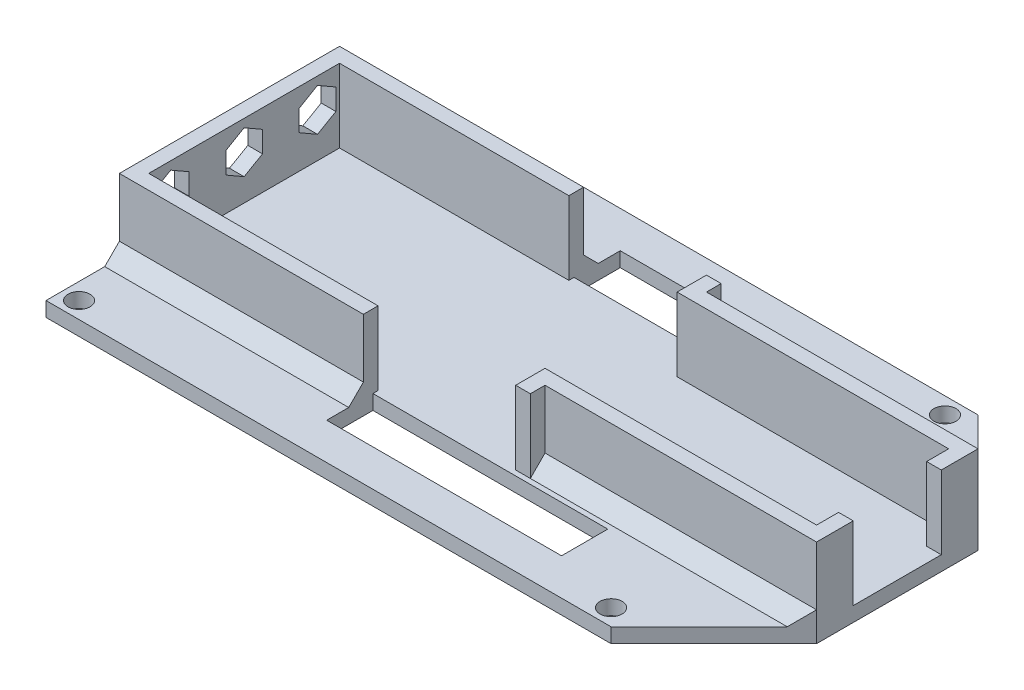
SolidWorks part; units mm, degrees
ref_plane "Front Plane" through (0, 0, 0) normal (0, 0, 1) x (1, 0, 0)
ref_plane "Top Plane" through (0, 0, 0) normal (0, 1, 0) x (1, 0, 0)
ref_plane "Right Plane" through (0, 0, 0) normal (1, 0, 0) x (0, 0, -1)
sketch "Sketch1" plane through (0, 0, 0) normal (0, 1, 0) x (1, 0, 0)
  line L0 (0, 25) -> (0, -25) construction
  line L1 (-38.5, -25) -> (38.5, -25)
  line L2 (-38.5, -25) -> (-38.5, 25)
  line L3 (-38.5, 25) -> (38.5, 25)
  line L4 (38.5, -25) -> (38.5, 25)
  line L5 (-38.5, -25) -> (38.5, 25) construction
  line L6 (-38.5, 25) -> (38.5, -25) construction
  line L7 (-38.5, 0) -> (38.5, 0) construction
  line L8 (-33.5, 20) -> (33.5, 20) construction
  line L9 (33.5, -20) -> (33.5, 20) construction
  line L10 (-33.5, -20) -> (33.5, -20) construction
  line L11 (-33.5, -20) -> (-33.5, 20) construction
  line L12 (26.75, 13.7) -> (-5.25, 13.7)
  line L13 (26.75, -20) -> (-5.25, -20)
  line L14 (26.75, -20) -> (26.75, -13.7)
  line L15 (26.75, -13.7) -> (-5.25, -13.7)
  line L16 (-5.25, -20) -> (-5.25, -13.7)
  line L17 (-5.25, 20) -> (-5.25, 13.7)
  line L18 (26.75, 20) -> (-5.25, 20)
  line L19 (26.75, 20) -> (26.75, 13.7)
  circle A1 centre (-36.25, 22.75) radius 1.5
  circle A2 centre (36.25, 22.75) radius 1.5
  circle A3 centre (36.25, -22.75) radius 1.5
  circle A4 centre (-36.25, -22.75) radius 1.5
  point P0 (0, 0)
  dimension "D3" = 3
  dimension "D4" = 2.25
  dimension "D1" = 77
  dimension "D2" = 50
  dimension "D5" = 2.25
  dimension "D6" = 5
  dimension "D7" = 6.75
  dimension "D8" = 32
  dimension "D9" = 6.3
extrude "Boss-Extrude1" add sketch "Sketch1" along normal blind 2
sketch "Sketch2" plane through (0, 2, 0) normal (0, 1, 0) x (1, 0, 0)
  line L0 (-38.5, 0) -> (38.5, 0) construction
  line L1 (-38.5, 25) -> (-38.5, -25) construction
  line L2 (38.5, -25) -> (38.5, 25) construction
  line L3 (-38.5, -15) -> (-38.5, 15)
  line L4 (-36.5, -13) -> (13.5, -13)
  line L5 (-36.5, -13) -> (-36.5, 13)
  line L6 (-36.5, 13) -> (13.5, 13)
  line L7 (13.5, -13) -> (13.5, -9)
  line L8 (-36.5, -13) -> (13.5, 13) construction
  line L9 (-36.5, 13) -> (13.5, -13) construction
  line L10 (-38.5, 15) -> (-5.25, 15)
  line L11 (15.5, -13) -> (15.5, -11)
  line L12 (-38.5, -15) -> (-5.25, -15)
  line L13 (-5.25, 13) -> (-5.25, 15)
  line L14 (-5.25, 20) -> (-5.25, 13.7) construction
  line L15 (-5.25, -15) -> (-5.25, -13)
  line L16 (13.5, 13) -> (15.5, 13)
  line L17 (13.5, -13) -> (15.5, -13)
  line L18 (-38.5, -15) -> (15.5, -15) construction
  line L19 (15.5, -15) -> (15.5, 15) construction
  line L20 (-38.5, 15) -> (15.5, 15) construction
  line L22 (13.5, -9) -> (50.5, -9)
  line L24 (13.5, 9) -> (50.5, 9)
  line L25 (50.5, -9) -> (50.5, -6)
  line L26 (13.5, -9) -> (50.5, 9) construction
  line L27 (13.5, 9) -> (50.5, -9) construction
  line L29 (52.5, -11) -> (52.5, -6)
  line L31 (15.5, 11) -> (52.5, 11)
  line L32 (11.5, 11) -> (52.5, 11) construction
  line L33 (15.5, -11) -> (52.5, -11)
  line L34 (11.5, -11) -> (52.5, -11) construction
  line L35 (11.5, -11) -> (11.5, 11) construction
  line L36 (15.5, 11) -> (15.5, 13)
  line L37 (50.5, 6) -> (50.5, 9)
  line L38 (50.5, -6) -> (52.5, -6)
  line L39 (13.5, 9) -> (13.5, 13)
  line L40 (13.5, -13) -> (13.5, 13) construction
  line L41 (13.5, -9) -> (13.5, 9) construction
  line L43 (50.5, 6) -> (52.5, 6)
  line L47 (50.5, -9) -> (50.5, 9) construction
  line L48 (52.5, 6) -> (52.5, 11)
  line L49 (52.5, -11) -> (52.5, 11) construction
  point P6 (-11.5, 0)
  point P21 (32, 0)
  point P33 (50.5, 0)
  line M23 (-5.25, -20) -> (-5.25, -13.7)
  line M25 (38.5, -25) -> (38.5, 25)
  line M27 (-38.5, 25) -> (-38.5, -25)
  line M35 (-5.25, 13.7) -> (-5.25, 20)
  dimension "D1" = 26
  dimension "D2" = 50
  dimension "D3" = 2
  dimension "D5" = 2
  dimension "D4" = 2
extrude "Boss-Extrude2" add sketch "Sketch2" along normal blind 10 contours L15 L4 L5 L6 L13 L10 L12 M23 M35 M27 | L39 L24 L31 L36 L16 M25 | L43 L48 L31 L24 L37 M25 | L38 L25 L22 L33 L29 M25 | L11 L33 L22 L7 L17 M25
sketch "Sketch3" plane through (0, 2, 0) normal (0, -1, 0) x (1, 0, 0)
  line L0 (38.5, 25) -> (52.5, 11)
  line L1 (52.5, 11) -> (52.5, -11)
  line L2 (52.5, -11) -> (38.5, -25)
  line L3 (38.5, -25) -> (38.5, 25)
extrude "Boss-Extrude3" add sketch "Sketch3" along normal blind 2
chamfer "Chamfer1" distance 2 angle 45 4 edges at (-21.875, 2, -15) (34, 2, -11) (34, 2, 11) (-21.875, 2, 15)
sketch "Sketch4" plane through (-38.5, 0, 0) normal (-1, 0, 0) x (0, 0, 1)
  line L0 (0, 0) -> (0, 12)
  line L1 (-25, 0) -> (25, 0) construction
  line L2 (-15, 12) -> (15, 12) construction
  line L3 (10, 10.8868) -> (7.5, 9.4434)
  line L4 (0, 10.8868) -> (-2.5, 9.4434)
  line L5 (-2.5, 9.4434) -> (-2.5, 6.5566)
  line L6 (-2.5, 6.5566) -> (0, 5.1132)
  line L7 (0, 5.1132) -> (2.5, 6.5566)
  line L8 (2.5, 6.5566) -> (2.5, 9.4434)
  line L9 (2.5, 9.4434) -> (0, 10.8868)
  line L10 (7.5, 9.4434) -> (7.5, 6.5566)
  line L11 (7.5, 6.5566) -> (10, 5.1132)
  line L12 (10, 5.1132) -> (12.5, 6.5566)
  line L13 (12.5, 6.5566) -> (12.5, 9.4434)
  line L14 (12.5, 9.4434) -> (10, 10.8868)
  line L15 (-10, 10.8868) -> (-12.5, 9.4434)
  line L16 (-12.5, 9.4434) -> (-12.5, 6.5566)
  line L17 (-12.5, 6.5566) -> (-10, 5.1132)
  line L18 (-10, 5.1132) -> (-7.5, 6.5566)
  line L19 (-7.5, 6.5566) -> (-7.5, 9.4434)
  line L20 (-7.5, 9.4434) -> (-10, 10.8868)
  circle A0 centre (0, 8) radius 2.5 construction
  dimension "D1" = 5
  dimension "D2" = 4
  dimension "D3" = 2
  dimension "D4" = 2
extrude "Cut-Extrude1" cut sketch "Sketch4" against normal up to next contours L19 L20 L15 L16 L17 L18 | L8 L9 L0 L7 | L5 L6 L0 L4 | L13 L14 L3 L10 L11 L12
